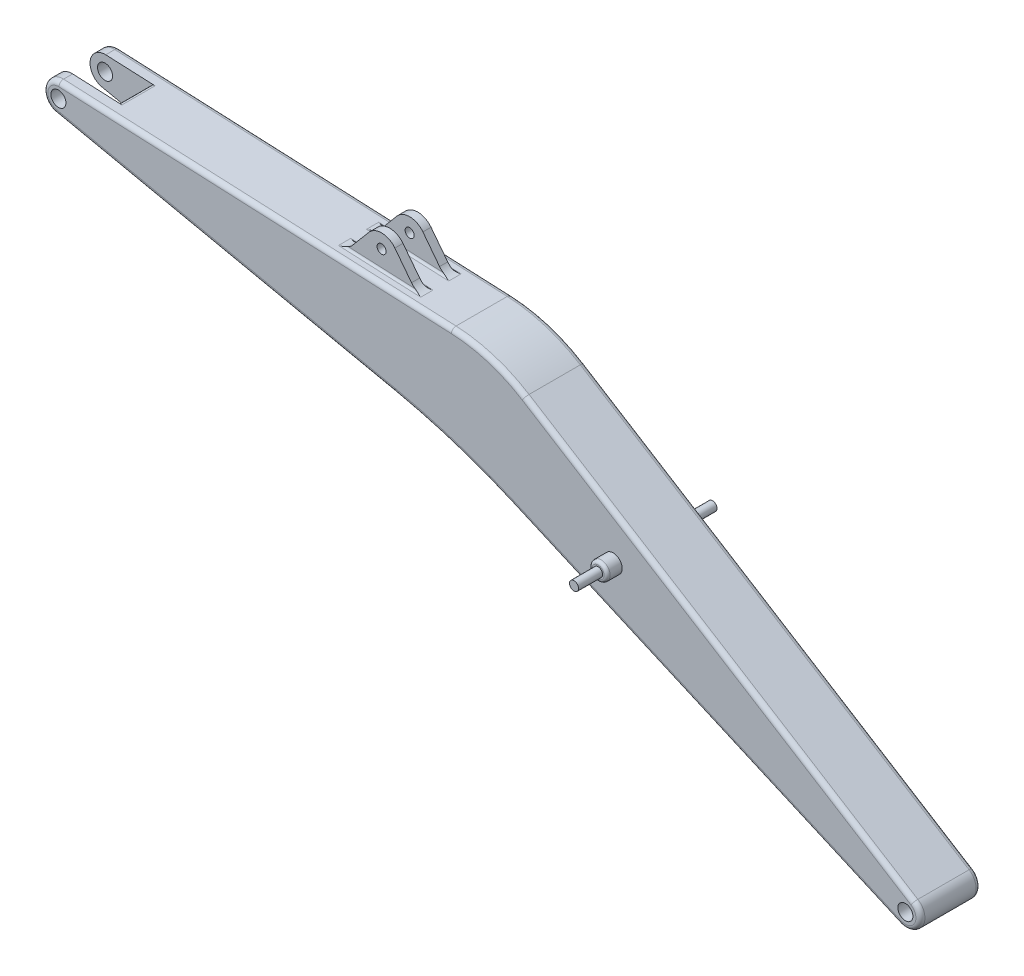
SolidWorks part; units mm, degrees
material "AISI 1020"
ref_plane "Front" through (0, 0, 0) normal (0, 0, 1) x (1, 0, 0)
ref_plane "Top" through (0, 0, 0) normal (0, 1, 0) x (1, 0, 0)
ref_plane "Right" through (0, 0, 0) normal (1, 0, 0) x (0, 0, -1)
sketch "Sketch1" plane through (0, 0, 0) normal (0, 0, 1) x (1, 0, 0)
  line L0 (0, -246.8451) -> (4466.049, -246.8451) construction
  line L1 (0, -50) -> (0, 50) construction
  line L2 (4.161, 1419.7742) -> (3124.8839, 1280.1503)
  line L3 (3124.8839, 1280.1503) -> (4824.1532, 218.4544)
  line L4 (4.161, 1074.0395) -> (2819.6688, 475.5848)
  line L5 (2819.6688, 475.5848) -> (4595.1269, -303.4844)
  line L6 (4553.8199, -246.8451) -> (4826, -246.8451) construction
  line L7 (4824.1532, 218.4544) -> (4595.1269, -303.4844)
  line L8 (4.161, 1074.0395) -> (4.161, 1419.7742)
  arc A0 (25.1135, 1418.8367) -> (4.161, 1419.7742) centre (4.161, 1185.1522) ccw
  dimension "D2" = 102
  dimension "D1" = 4826
extrude "Boss-Extrude1" add sketch "Sketch1" along normal blind 508
fillet "Fillet1" radius 1270 1 edges at (3124.8839, 1280.1503, 254)
fillet "Fillet2" radius 5080 1 edges at (2819.6688, 475.5848, 254)
sketch "Sketch2" plane through (0, 0, 508) normal (0, 0, 1) x (1, 0, 0)
  line L0 (4824.1532, 218.4544) -> (6687.1578, -945.5424)
  line L1 (4595.1269, -303.4844) -> (6568.833, -1169.5446)
  line L2 (4595.1269, -303.4844) -> (4824.1532, 218.4544)
  line L6 (4.161, 1074.0395) -> (2310.9144, 583.7239) construction
  line L7 (4.161, 1419.7742) -> (2791.622, 1295.0607) construction
  line L8 (-519.138, 1443.187) -> (4.161, 1419.7742)
  line L9 (3295.9534, 266.5917) -> (4595.1269, -303.4844) construction
  line L10 (3407.7981, 1103.3867) -> (4824.1532, 218.4544) construction
  line L11 (-551.2192, 1192.0892) -> (4.161, 1074.0395)
  line L12 (4.161, 1074.0395) -> (4.161, 1419.7742)
  arc A0 (6568.833, -1169.5446) -> (6687.1578, -945.5424) centre (6619.8637, -1053.2481) ccw
  arc A1 (-519.138, 1443.187) -> (-551.2192, 1192.0892) centre (-524.8144, 1316.314) ccw
  circle A2 centre (6619.8637, -1053.2481) radius 63.5
  circle A3 centre (-524.8144, 1316.314) radius 63.5
  dimension "D1" = 127
  dimension "D2" = 127
  dimension "D3" = 127
  dimension "D4" = 127
extrude "Boss-Extrude2" add sketch "Sketch2" against normal blind 508
sketch "Sketch8" plane through (0, 0, 508) normal (0, 0, 1) x (1, 0, 0)
  circle A0 centre (4154.8472, 262.0958) radius 76.2
  circle A1 centre (6619.8637, -1053.2481) radius 63.5 construction
  dimension "D1" = 152.4
  dimension "D2" = 2794
fillet "Fillet7" radius 38.1 16 edges at (-650.7904, 1332.4091, 508) (-650.7904, 1332.4091, 0) (879.8476, 887.9066, 0) (2811.5302, 450.3056, 0) (4932.3932, -451.4765, 0) (6732.1596, -1112.5662, 508) (6732.1596, -1112.5662, 0) (5047.4779, 78.9221, 0) (3112.087, 1239.0121, 0) (1136.242, 1369.1239, 0) (4932.3932, -451.4765, 508) (2811.5302, 450.3056, 508) (879.8476, 887.9066, 508) (1136.242, 1369.1239, 508) (3112.087, 1239.0121, 508) (5047.4779, 78.9221, 508)
sketch "Sketch9" plane through (63.4034, 1417.1236, 0) normal (0.0447, 0.999, 0) x (0.999, -0.0447, 0)
  line L0 (-583.1241, -254) -> (6722.7369, -254) construction
  line L2 (-583.1241, -38.1) -> (-583.1241, -469.9) construction
  line L3 (6722.7369, -38.1) -> (6722.7369, -469.9) construction
extrude "Boss-Extrude3" add sketch "Sketch8" along normal blind 127 contours A0
ref_plane "Plane2" through (0, 0, 254) normal (0, 0, 1) x (1, 0, 0)
mirror "Mirror1" about plane through (0, 0, 254) normal (0, 0, 1) of "Boss-Extrude3"
sketch "Sketch10" plane through (0, 0, 254) normal (0, 0, 1) x (1, 0, 0)
  line L1 (1816.197, 1338.7021) -> (2388.5274, 1313.0955)
  line L3 (1991.8863, 1547.437) -> (1816.197, 1338.7021)
  line L4 (2212.0689, 1542.5775) -> (2388.5274, 1313.0955)
  line L5 (-519.138, 1443.187) -> (2791.622, 1295.0607) construction
  line L6 (-519.138, 1443.187) -> (2791.622, 1295.0607) construction
  arc A0 (1991.8863, 1547.437) -> (2212.0689, 1542.5775) centre (2100.0225, 1456.4203) cw
  circle A2 centre (2100.0225, 1480.0328) radius 38.1
  dimension "D1" = 76.2
extrude "Boss-Extrude4" add sketch "Sketch10" along normal mid plane 304.8
sketch "Sketch11" plane through (63.4034, 1417.1236, 0) normal (0.0447, 0.999, 0) x (0.999, -0.0447, 0)
  line L0 (1754.5471, -254) -> (2444.8844, -254) construction
  line L1 (1642.5117, -170.0535) -> (2403.2568, -170.0535)
  line L2 (1642.5117, -170.0535) -> (1642.5117, -337.9465)
  line L3 (1642.5117, -337.9465) -> (2403.2568, -337.9465)
  line L4 (2403.2568, -170.0535) -> (2403.2568, -337.9465)
  line L5 (1754.5471, -406.4) -> (1754.5471, -101.6) construction
extrude "Cut-Extrude10" cut sketch "Sketch11" along normal blind 304.8 contours L4 L3 L2 L1
fillet "Fillet8" radius 127 4 edges at (1816.197, 1338.7021, 135.8267) (1816.197, 1338.7021, 372.1733) (2388.5274, 1313.0955, 135.8267) (2388.5274, 1313.0955, 372.1733)
fillet "Fillet9" radius 17.78 4 edges at (2100.5962, 1325.9778, 406.4) (2100.5962, 1325.9778, 337.9465) (2100.5962, 1325.9778, 101.6) (2100.5962, 1325.9778, 170.0535)
sketch "Sketch12" plane through (63.4034, 1417.1236, 0) normal (0.0447, 0.999, 0) x (0.999, -0.0447, 0)
  line L0 (-710.1241, -38.1) -> (-710.1241, -469.9) construction
  line L1 (-1218.1241, -114.3) -> (-202.1241, -114.3)
  line L2 (-1218.1241, -114.3) -> (-1218.1241, -393.7)
  line L3 (-1218.1241, -393.7) -> (-202.1241, -393.7)
  line L4 (-202.1241, -114.3) -> (-202.1241, -393.7)
  line L5 (-1218.1241, -114.3) -> (-202.1241, -393.7) construction
  line L6 (-1218.1241, -393.7) -> (-202.1241, -114.3) construction
  point P0 (-710.1241, -254)
  dimension "D1" = 279.4
  dimension "D2" = 1016
extrude "Cut-Extrude11" cut sketch "Sketch12" against normal through all both and the other way through all
fillet "Fillet10" radius 35.56 2 edges at (-152.7804, 1107.3984, 254) (-138.5188, 1426.1578, 254)
sketch "Sketch13" plane through (0, 0, 635) normal (0, 0, 1) x (1, 0, 0)
  circle A0 centre (4154.8472, 262.0958) radius 38.1
  dimension "D1" = 76.2
extrude "Boss-Extrude5" add sketch "Sketch13" along normal blind 203.2
mirror "Mirror3" about plane through (0, 0, 254) normal (0, 0, 1) of "Boss-Extrude5"
fillet "Fillet11" radius 25.4 2 edges at (4231.0472, 262.0958, 635) (4231.0472, 262.0958, -127)
